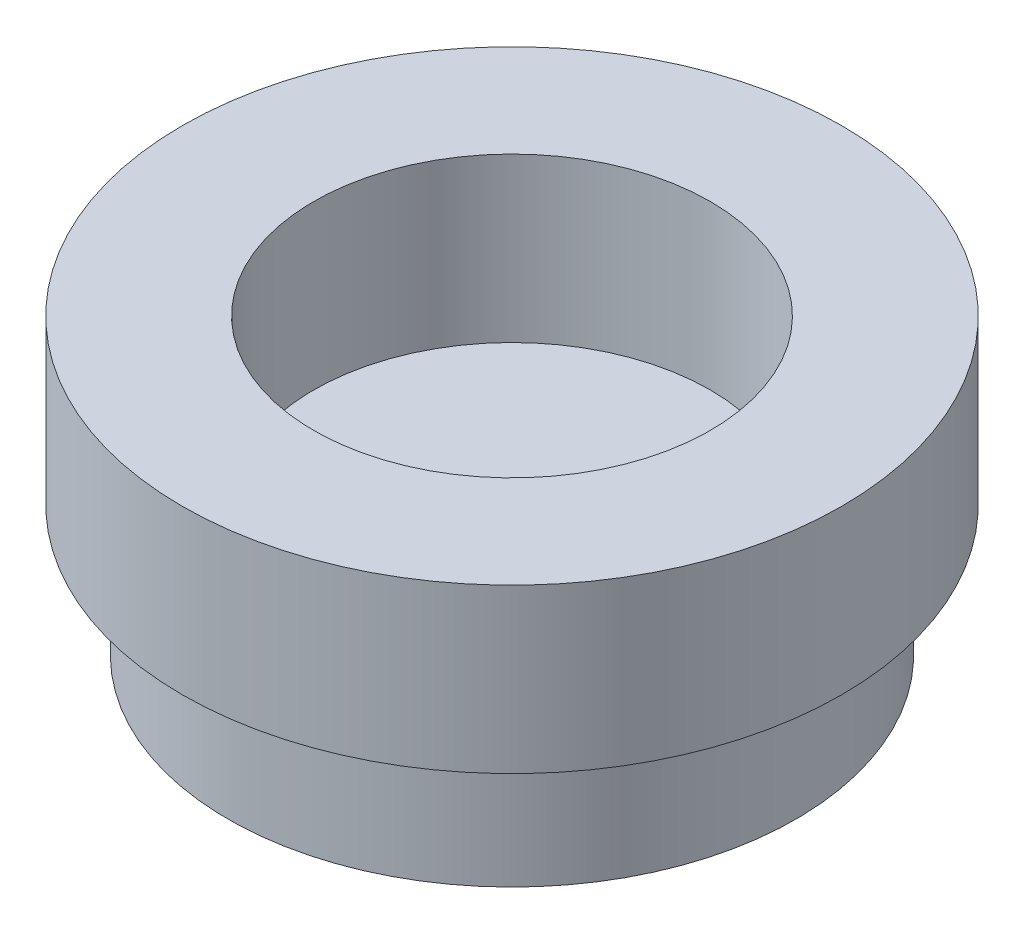
SolidWorks part; units mm, degrees
ref_plane "Front Plane" through (0, 0, 0) normal (0, 0, 1) x (1, 0, 0)
ref_plane "Top Plane" through (0, 0, 0) normal (0, 1, 0) x (1, 0, 0)
ref_plane "Right Plane" through (0, 0, 0) normal (1, 0, 0) x (0, 0, -1)
sketch "Sketch1" plane through (0, 0, 0) normal (0, 0, 1) x (1, 0, 0)
  line L0 (0, 0) -> (-4.35, 0)
  line L1 (55, 0) -> (-55, 0) construction
  line L2 (-4.35, 0) -> (-4.35, 2)
  line L3 (-4.35, 2) -> (-5.05, 2)
  line L4 (-5.05, 2) -> (-5.05, 4.5)
  line L5 (-5.05, 4.5) -> (-3.0375, 4.5)
  line L6 (-3.0375, 4.5) -> (-3.0375, 2)
  line L7 (-3.0375, 2) -> (0, 2)
  line L8 (0, -55) -> (0, 55) construction
  line L9 (0, 2) -> (0, 0)
  line L10 (0, 0) -> (0, 7.0876) construction
  point P9 (-3.0375, 3.25)
  dimension "D1" = 4.35
  dimension "D2" = 2
  dimension "D3" = 5.05
  dimension "D4" = 4.5
  dimension "D5" = 3.0375
  dimension "D6" = 2
revolve "Revolve1" add sketch "Sketch1" angle 360 about L10
